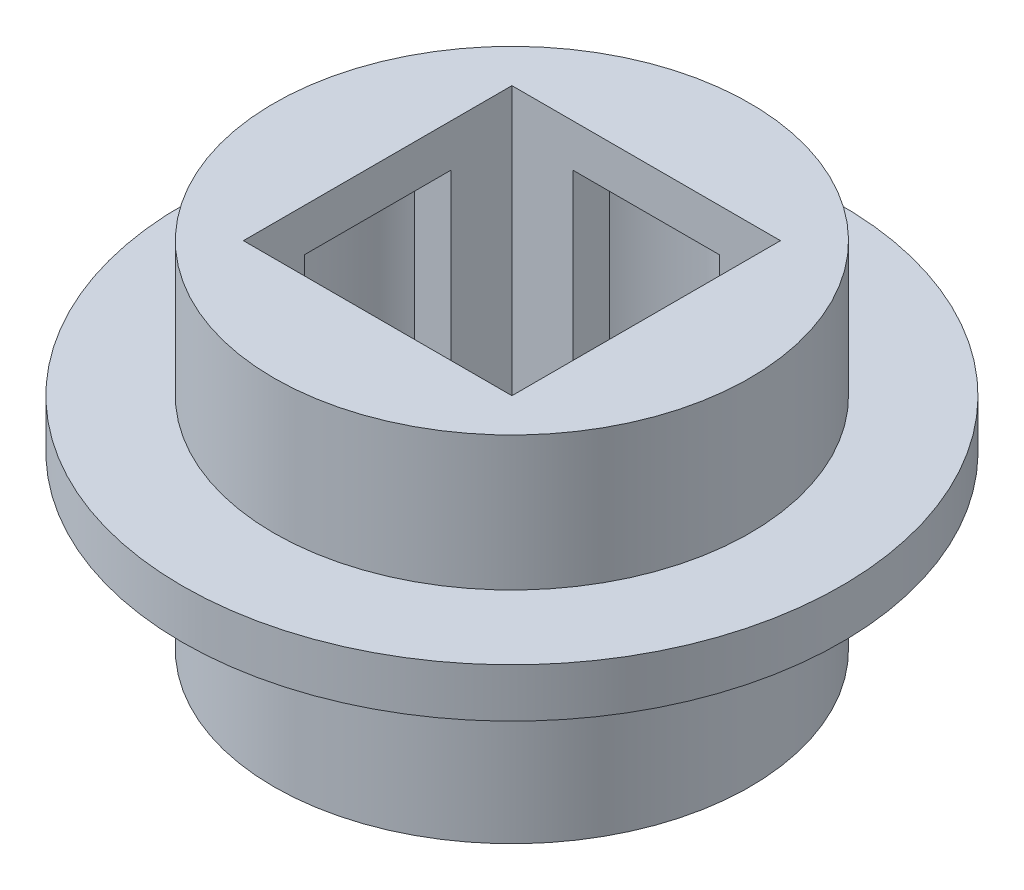
SolidWorks part; units mm, degrees
material "ABS"
ref_plane "Front Plane" through (0, 0, 0) normal (0, 0, 1) x (1, 0, 0)
ref_plane "Top Plane" through (0, 0, 0) normal (0, 1, 0) x (1, 0, 0)
ref_plane "Right Plane" through (0, 0, 0) normal (1, 0, 0) x (0, 0, -1)
sketch "Sketch1" plane through (0, 0, 0) normal (0, 1, 0) x (1, 0, 0)
  circle A0 centre (0, 0) radius 27
  circle A1 centre (0, 0) radius 19.5
extrude "Boss-Extrude1" add sketch "Sketch1" along normal blind 4
sketch "Sketch2" plane through (0, 4, 0) normal (0, 1, 0) x (1, 0, 0)
  circle A0 centre (0, 0) radius 19.5
extrude "Boss-Extrude2" add sketch "Sketch2" along normal blind 11 and the other way blind 18 separate body
sketch "Sketch3" plane through (0, 15, 0) normal (0, 1, 0) x (1, 0, 0)
  line L1 (-11, -11) -> (11, -11)
  line L2 (-11, -11) -> (-11, 11)
  line L3 (-11, 11) -> (11, 11)
  line L4 (11, -11) -> (11, 11)
  line L5 (-11, -11) -> (11, 11) construction
  line L6 (-11, 11) -> (11, -11) construction
  point P0 (0, 0)
extrude "Cut-Extrude1" cut sketch "Sketch3" against normal up to next (29 mm away)
sketch "Sketch4" plane through (0, -14, 0) normal (0, -1, 0) x (1, 0, 0)
  line L0 (11, 6) -> (11, -6)
  line L1 (11, 11) -> (-11, 11) construction
  line L2 (-6, 11) -> (6, 11)
  line L3 (-6, 11) -> (-6, 14)
  line L4 (6, 11) -> (6, 14)
  line L5 (11, 6) -> (14, 6)
  line L6 (11, -6) -> (14, -6)
  line L7 (6, -11) -> (-6, -11)
  line L8 (6, -11) -> (6, -14)
  line L9 (-6, -11) -> (-6, -14)
  line L10 (-11, -6) -> (-11, 6)
  line L11 (-11, -6) -> (-14, -6)
  line L12 (-11, 6) -> (-14, 6)
  arc A0 (-6, 14) -> (6, 14) centre (0, 8) cw
  arc A1 (14, 6) -> (14, -6) centre (8, 0) cw
  arc A2 (6, -14) -> (-6, -14) centre (0, -8) cw
  arc A3 (-14, -6) -> (-14, 6) centre (-8, 0) cw
  point P8 (0, 11)
  point P16 (11, 0)
  point P22 (0, -11)
  point P28 (-11, 0)
  point P31 (0, 0)
  dimension "D1" = 4
extrude "Cut-Extrude2" cut sketch "Sketch4" against normal blind 25.5
